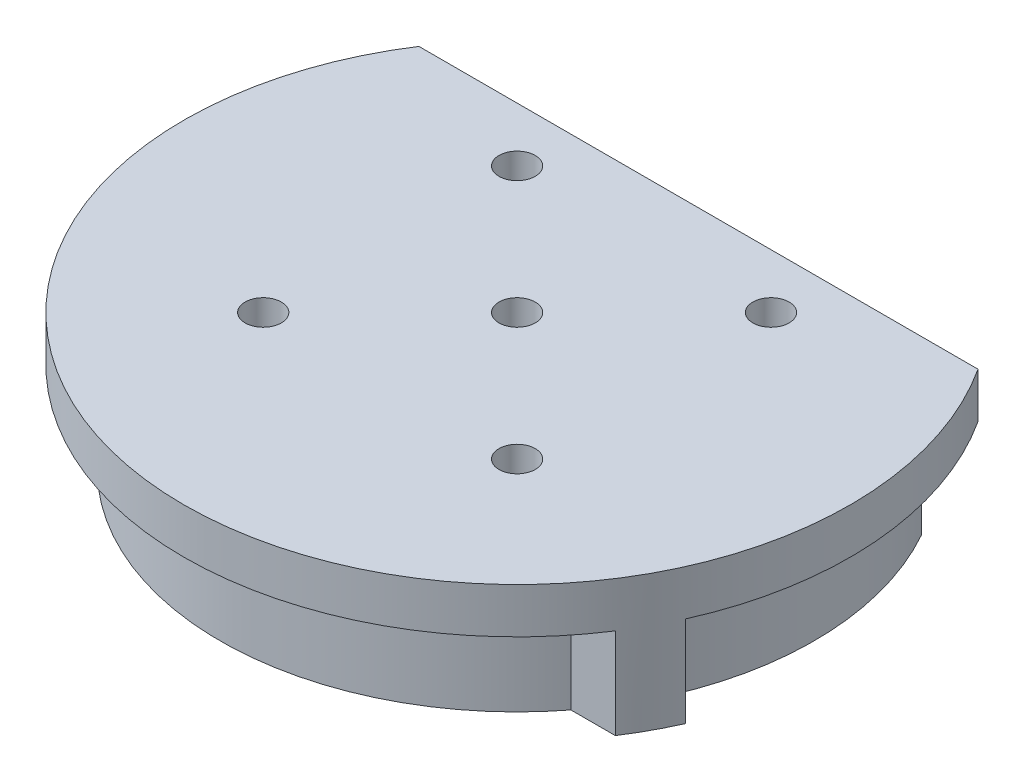
SolidWorks part; units mm, degrees
ref_plane "Спереди" through (0, 0, 0) normal (0, 0, 1) x (1, 0, 0)
ref_plane "Сверху" through (0, 0, 0) normal (0, 1, 0) x (1, 0, 0)
ref_plane "Справа" through (0, 0, 0) normal (1, 0, 0) x (0, 0, -1)
sketch "Эскиз1" plane through (0, 0, 0) normal (0, 1, 0) x (1, 0, 0)
  circle A0 centre (0, 0) radius 2
  circle A1 centre (0, 0) radius 7.5
  dimension "D1" = 15
  dimension "D2" = 4
extrude "cylinder" add sketch "Эскиз1" along normal blind 5 and the other way blind 10
sketch "Эскиз2" plane through (0, 0, 0) normal (0, 1, 0) x (1, 0, 0)
  circle A0 centre (0, 0) radius 36.75
  circle A1 centre (0, 0) radius 2.5
  dimension "D1" = 73.5
  dimension "D2" = 5
extrude "base horizont" add sketch "Эскиз2" along normal blind 5
sketch "Эскиз3" plane through (0, 5, 0) normal (0, 1, 0) x (1, 0, 0)
  circle A0 centre (0, 0) radius 28.75
  circle A1 centre (0, 0) radius 32.75
  dimension "D1" = 57.5
  dimension "D2" = 65.5
extrude "edge" add sketch "Эскиз3" against normal blind 15
sketch "Эскиз8" plane through (0, 0, 0) normal (0, 1, 0) x (1, 0, 0)
  line L1 (-30.8312, 36.75) -> (30.8312, 36.75)
  line L2 (-30.8312, 36.75) -> (-30.8312, 20)
  line L3 (-30.8312, 20) -> (30.8312, 20)
  line L4 (30.8312, 36.75) -> (30.8312, 20)
  circle A1 centre (0, 0) radius 36.75 construction
  dimension "D1" = 20
extrude "cutoff" cut sketch "Эскиз8" against normal blind 10 and the other way blind 10
sketch "Эскиз12" plane through (0, -10, 0) normal (0, -1, 0) x (1, 0, 0)
  line L0 (20.6534, -20) -> (-20.6534, -20) construction
  line L1 (-28.5756, -16) -> (-20.5756, -16)
  line L2 (-28.5756, -16) -> (-28.5756, -20)
  line L3 (-28.5756, -20) -> (-20.5756, -20)
  line L4 (-20.5756, -16) -> (-20.5756, -20)
  line L6 (28.5756, -16) -> (20.5756, -16)
  line L7 (28.5756, -16) -> (28.5756, -20)
  line L8 (28.5756, -20) -> (20.5756, -20)
  line L9 (20.5756, -16) -> (20.5756, -20)
  arc A0 (25.9338, -20) -> (-25.9338, -20) centre (0, 0) ccw construction
  dimension "D1" = 4
  dimension "D2" = 8
extrude "Вытянуть1" cut sketch "Эскиз12" against normal blind 10
sketch "Эскиз13" plane through (0, 0, 0) normal (0, -1, 0) x (1, 0, 0)
  line L0 (-30.8312, 20) -> (-25.9338, 20)
  line L1 (-45, 20) -> (45, 20) construction
  line L2 (-45, 20) -> (-45, 15) construction
  line L3 (-45, 15) -> (45, 15) construction
  line L4 (45, 20) -> (45, 15) construction
  line L5 (-33.5494, 15) -> (-29.1129, 15)
  line L6 (0, 0) -> (0, 36.75) construction
  line L7 (33.5494, 15) -> (29.1129, 15)
  line L8 (30.8312, 20) -> (25.9338, 20)
  arc A0 (30.8312, -20) -> (-30.8312, -20) centre (0, 0) ccw construction
  arc A1 (28.5756, -16) -> (-28.5756, -16) centre (0, 0) ccw construction
  arc A2 (28.5756, -16) -> (-28.5756, -16) centre (0, 0) ccw construction
  arc A3 (-33.5494, 15) -> (-30.8312, 20) centre (0, 0) cw
  arc A4 (-29.1129, 15) -> (-25.9338, 20) centre (0, 0) cw
  arc A5 (29.1129, 15) -> (25.9338, 20) centre (0, 0) ccw
  arc A6 (33.5494, 15) -> (30.8312, 20) centre (0, 0) ccw
  point P4 (0, 15)
  dimension "D1" = 5
  dimension "D2" = 90
  dimension "D3" = 15
extrude "Вытянуть2" add sketch "Эскиз13" along normal blind 10
sketch "Эскиз14" plane through (0, 5, 0) normal (0, 1, 0) x (1, 0, 0)
  line L1 (-14, 14) -> (14, 14) construction
  line L2 (-14, 14) -> (-14, -14) construction
  line L3 (-14, -14) -> (14, -14) construction
  line L4 (14, 14) -> (14, -14) construction
  circle A0 centre (14, -14) radius 2
  circle A2 centre (-14, -14) radius 2
  circle A3 centre (-14, 14) radius 2
  circle A4 centre (14, 14) radius 2
  point P4 (14, 0)
  point P5 (0, 14)
  dimension "D2" = 4
  dimension "D1" = 28
extrude "Вытянуть3" cut sketch "Эскиз14" against normal blind 10
